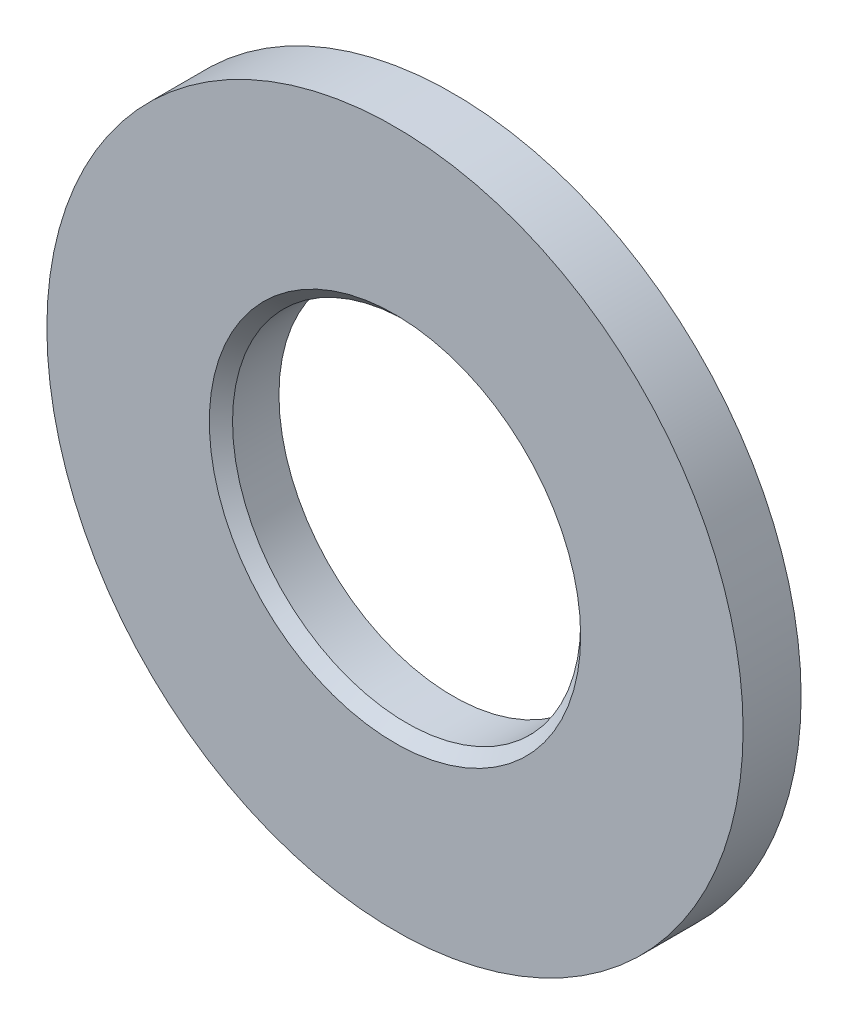
SolidWorks part; units mm, degrees
ref_plane "Спереди" through (0, 0, 0) normal (0, 0, 1) x (1, 0, 0)
ref_plane "Сверху" through (0, 0, 0) normal (0, 1, 0) x (1, 0, 0)
ref_plane "Справа" through (0, 0, 0) normal (1, 0, 0) x (0, 0, -1)
sketch "Эскиз1" plane through (0, 0, 0) normal (0, 0, 1) x (1, 0, 0)
  circle A0 centre (0, 0) radius 6
  circle A1 centre (0, 0) radius 3
extrude "Бобышка-Вытянуть1" add sketch "Эскиз1" along normal blind 1
chamfer "Фаска1" distance 0.2 angle 45 1 edges at (3, 0, 1)
